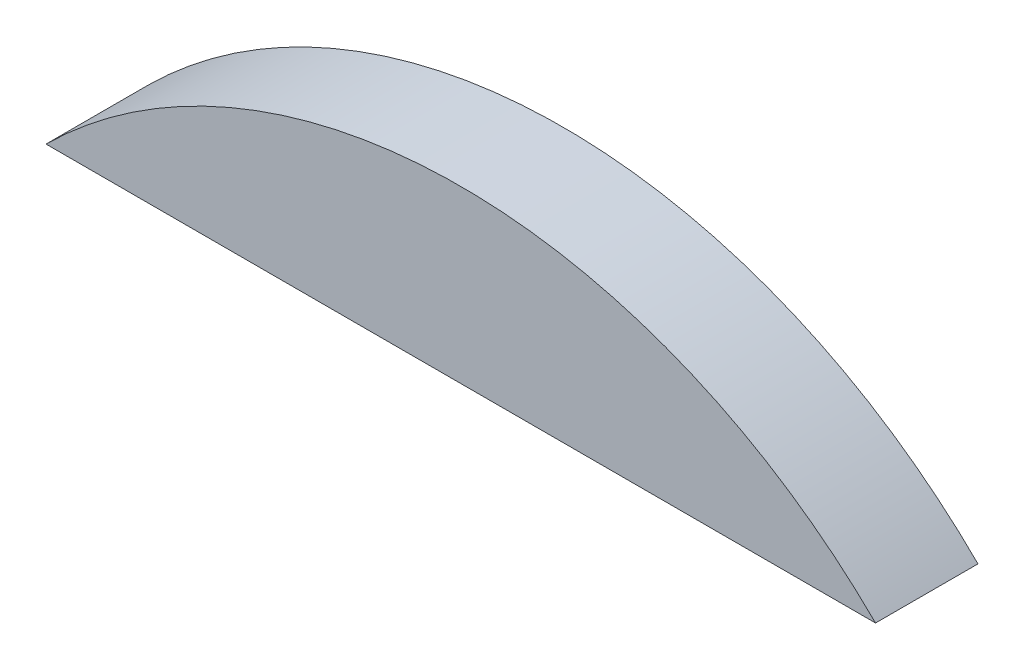
SolidWorks part; units mm, degrees
material "Pure Lead"
ref_plane "Front Plane" through (0, 0, 0) normal (0, 0, 1) x (1, 0, 0)
ref_plane "Top Plane" through (0, 0, 0) normal (0, 1, 0) x (1, 0, 0)
ref_plane "Right Plane" through (0, 0, 0) normal (1, 0, 0) x (0, 0, -1)
sketch "Sketch1" plane through (0, 0, 0) normal (0, 0, 1) x (1, 0, 0)
  line L0 (-121.4496, 122.5) -> (121.4496, 122.5)
  line L1 (0, 172.5) -> (0, 122.5)
  arc A0 (-121.4496, 122.5) -> (121.4496, 122.5) centre (0, 0) cw
  dimension "D1" = 172.5
  dimension "D2" = 50
extrude "Boss-Extrude1" add sketch "Sketch1" against normal blind 30 contours A0 L0 L1 | A0 L1 L0
